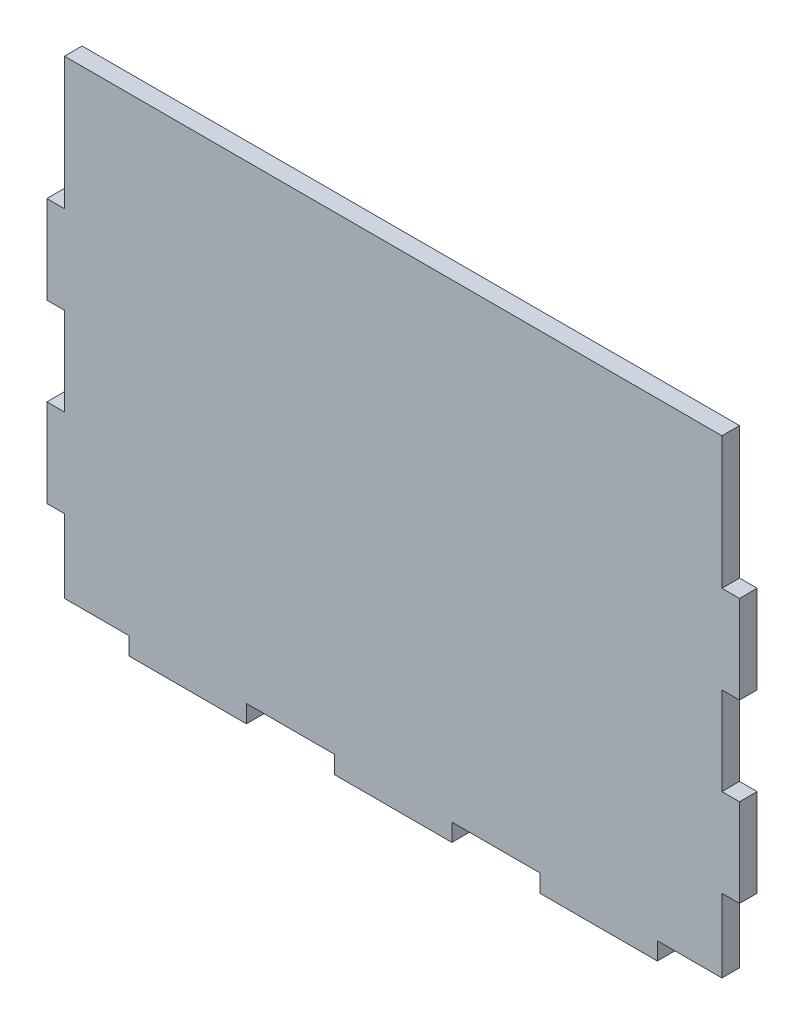
SolidWorks part; units mm, degrees
ref_plane "Front Plane" through (0, 0, 0) normal (0, 0, 1) x (1, 0, 0)
ref_plane "Top Plane" through (0, 0, 0) normal (0, 1, 0) x (1, 0, 0)
ref_plane "Right Plane" through (0, 0, 0) normal (1, 0, 0) x (0, 0, -1)
sketch "Sketch2" plane through (0, 0, 0) normal (0, 0, 1) x (1, 0, 0)
  line L0 (0, -55) -> (0, 55) construction
  line L1 (56, -40) -> (-56, -40)
  line L2 (56, -40) -> (56, 40)
  line L3 (56, 40) -> (-56, 40)
  line L4 (-56, -40) -> (-56, 40)
  line L5 (56, -40) -> (-56, 40) construction
  line L6 (56, 40) -> (-56, -40) construction
  line L7 (-10, -43) -> (10, -43)
  line L8 (-10, -43) -> (-10, -40)
  line L9 (-10, -40) -> (10, -40)
  line L10 (10, -43) -> (10, -40)
  line L11 (-10, -43) -> (10, -40) construction
  line L12 (-10, -40) -> (10, -43) construction
  line L13 (25, -43) -> (45, -43)
  line L14 (25, -43) -> (25, -40)
  line L15 (25, -40) -> (45, -40)
  line L16 (45, -43) -> (45, -40)
  line L17 (25, -43) -> (45, -40) construction
  line L18 (25, -40) -> (45, -43) construction
  line L19 (59, 2.5) -> (56, 2.5)
  line L20 (59, 2.5) -> (59, 17.5)
  line L21 (59, 17.5) -> (56, 17.5)
  line L22 (56, 2.5) -> (56, 17.5)
  line L23 (59, 2.5) -> (56, 17.5) construction
  line L24 (59, 17.5) -> (56, 2.5) construction
  line L25 (59, -27.5) -> (56, -27.5)
  line L26 (59, -27.5) -> (59, -12.5)
  line L27 (59, -12.5) -> (56, -12.5)
  line L28 (56, -27.5) -> (56, -12.5)
  line L29 (59, -27.5) -> (56, -12.5) construction
  line L30 (59, -12.5) -> (56, -27.5) construction
  line L31 (-59, 17.5) -> (-56, 17.5)
  line L32 (-56, 2.5) -> (-56, 17.5)
  line L33 (-59, 2.5) -> (-56, 2.5)
  line L34 (-59, 2.5) -> (-59, 17.5)
  line L35 (-59, -12.5) -> (-56, -12.5)
  line L36 (-56, -27.5) -> (-56, -12.5)
  line L37 (-59, -27.5) -> (-56, -27.5)
  line L38 (-59, -27.5) -> (-59, -12.5)
  line L39 (-25, -40) -> (-45, -40)
  line L40 (-45, -43) -> (-45, -40)
  line L41 (-25, -43) -> (-45, -43)
  line L42 (-25, -43) -> (-25, -40)
  line L43 (-10, -43) -> (-10, -40)
  line L44 (10, -43) -> (10, -40)
  line L46 (-56, -40) -> (56, -40)
  line L47 (-56, -40) -> (-56, 2.5)
  line L48 (-56, 2.5) -> (56, 2.5)
  line L49 (56, -40) -> (56, 2.5)
  point P0 (0, 0)
  point P6 (0, -41.5)
  point P11 (35, -41.5)
  point P16 (57.5, -20)
  point P17 (57.5, 10)
  point P40 (0, 0)
  dimension "D1" = 112
  dimension "D2" = 80
  dimension "D3" = 3
  dimension "D4" = 20
  dimension "D5" = 15
  dimension "D6" = 15
  dimension "D7" = 3
  dimension "D8" = 50
  dimension "D9" = 15
extrude "Boss-Extrude1" add sketch "Sketch2" along normal blind 3 contours L4 L1 L2 L3 | L41 L42 L1 L40 | L7 L10 L1 L8 | L13 L16 L1 L14
sketch "Sketch4" [suppressed] plane through (0, 0, 3) normal (0, 0, 1) x (1, 0, 0)
  line L0 (59, 7.5) -> (59, 22.5) construction
  line L1 (-59, 7.5) -> (59, 7.5)
  line L2 (-59, 7.5) -> (-59, 30)
  line L3 (-59, 30) -> (59, 30)
  line L4 (59, 7.5) -> (59, 30)
  line L5 (56, 30) -> (-56, 30) construction
  line L6 (0, -1.65) -> (0, 1.65) construction
  line L7 (-10, 4.5) -> (10, 4.5)
  line L8 (-10, 4.5) -> (-10, 7.5)
  line L9 (-10, 7.5) -> (10, 7.5)
  line L10 (10, 4.5) -> (10, 7.5)
  line L11 (-10, 4.5) -> (10, 7.5) construction
  line L12 (-10, 7.5) -> (10, 4.5) construction
  line L13 (-45, 4.5) -> (-25, 4.5)
  line L14 (-45, 4.5) -> (-45, 7.5)
  line L15 (-45, 7.5) -> (-25, 7.5)
  line L16 (-25, 4.5) -> (-25, 7.5)
  line L17 (-45, 4.5) -> (-25, 7.5) construction
  line L18 (-45, 7.5) -> (-25, 4.5) construction
  line L19 (45, 7.5) -> (25, 7.5)
  line L20 (25, 4.5) -> (25, 7.5)
  line L21 (45, 4.5) -> (25, 4.5)
  line L22 (45, 4.5) -> (45, 7.5)
  point P9 (0, 6)
  point P14 (-35, 6)
  line M15 (56, 7.5) -> (59, 7.5)
  line M16 (59, 7.5) -> (59, 22.5)
  line M17 (59, 22.5) -> (56, 22.5)
  line M18 (56, 22.5) -> (56, 30)
  line M19 (56, 30) -> (-56, 30)
  line M20 (-56, 30) -> (-56, 22.5)
  line M21 (-56, 22.5) -> (-59, 22.5)
  line M22 (-59, 22.5) -> (-59, 7.5)
  line M23 (-59, 7.5) -> (-56, 7.5)
  dimension "D1" = 3
  dimension "D2" = 20
  dimension "D3" = 15
extrude "Cut-Extrude2" [suppressed] cut sketch "Sketch4" against normal blind 10 contours L13 L16 L1 L14 | L7 L10 L1 L8 | L21 L22 L1 L20 | L1 M23 M15 M16 M17 M18 M19 M20 M21 M22
